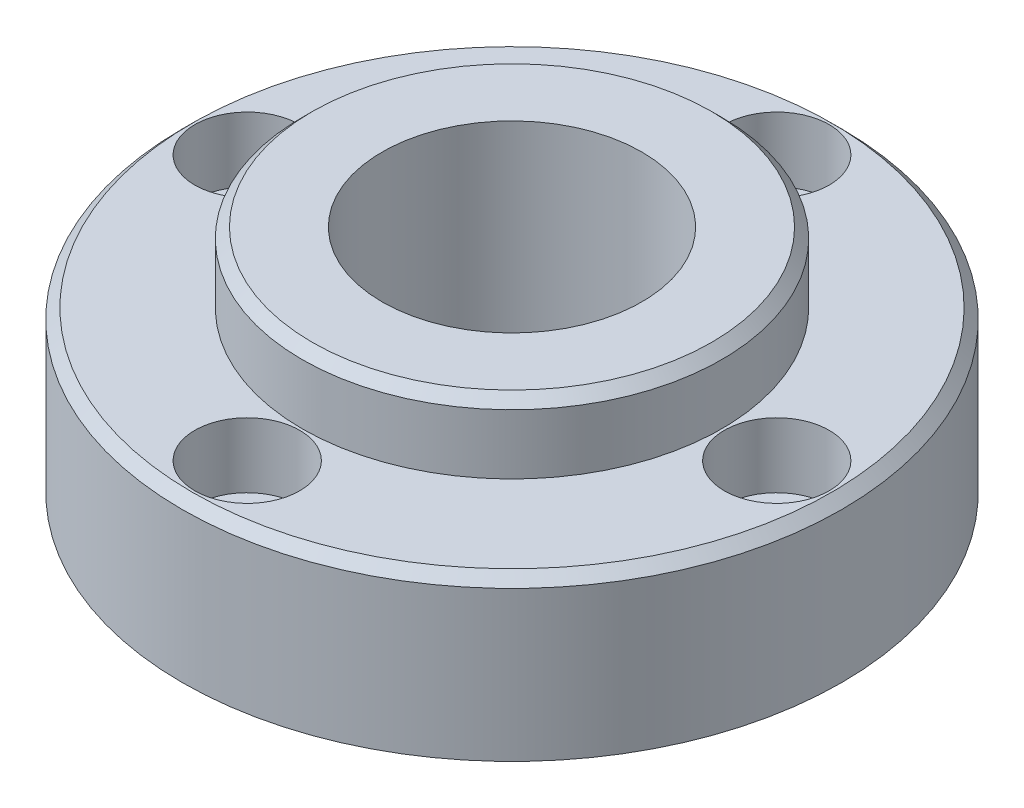
SolidWorks part; units mm, degrees
ref_plane "Alzado" through (0, 0, 0) normal (0, 0, 1) x (1, 0, 0)
ref_plane "Planta" through (0, 0, 0) normal (0, 1, 0) x (1, 0, 0)
ref_plane "Vista lateral" through (0, 0, 0) normal (1, 0, 0) x (0, 0, -1)
sketch "Croquis1" plane through (0, 0, 0) normal (0, 1, 0) x (1, 0, 0)
  circle A0 centre (0, 0) radius 33
  dimension "D1" = 66
extrude "Saliente-Extruir1" add sketch "Croquis1" along normal blind 16
sketch "Croquis2" plane through (0, 16, 0) normal (0, 1, 0) x (1, 0, 0)
  circle A0 centre (0, 0) radius 21
  dimension "D1" = 42
extrude "Saliente-Extruir2" add sketch "Croquis2" along normal blind 7
sketch "Croquis3" plane through (0, 0, 0) normal (0, -1, 0) x (1, 0, 0)
  circle A0 centre (0, 0) radius 17
  dimension "D1" = 34
extrude "Saliente-Extruir3" add sketch "Croquis3" along normal blind 1.5
sketch "Croquis4" plane through (0, 23, 0) normal (0, 1, 0) x (1, 0, 0)
  circle A0 centre (0, 0) radius 13
  dimension "D1" = 26
extrude "Cortar-Extruir1" cut sketch "Croquis4" against normal through all
chamfer "Chaflán1" distance 1 angle 45 1 edges at (0, 16, 33)
sketch "Croquis5" plane through (0, 16, 0) normal (0, 1, 0) x (1, 0, 0)
  circle A0 centre (26.5, 0) radius 5.25
  dimension "D1" = 10.5
  dimension "D2" = 26.5
extrude "Cortar-Extruir2" cut sketch "Croquis5" against normal blind 6.5
sketch "Croquis6" plane through (0, 9.5, 0) normal (0, 1, 0) x (1, 0, 0)
  circle A0 centre (26.5, 0) radius 3.25
  dimension "D1" = 6.5
extrude "Cortar-Extruir3" cut sketch "Croquis6" against normal through all
pattern_circular "MatrizC1" count 4 over 360 about axis through (0, 0, 0) along (0, 1, 0) of "Cortar-Extruir3", "Cortar-Extruir2"
chamfer "Chaflán2" distance 1 angle 45 1 edges at (0, 23, 21)
